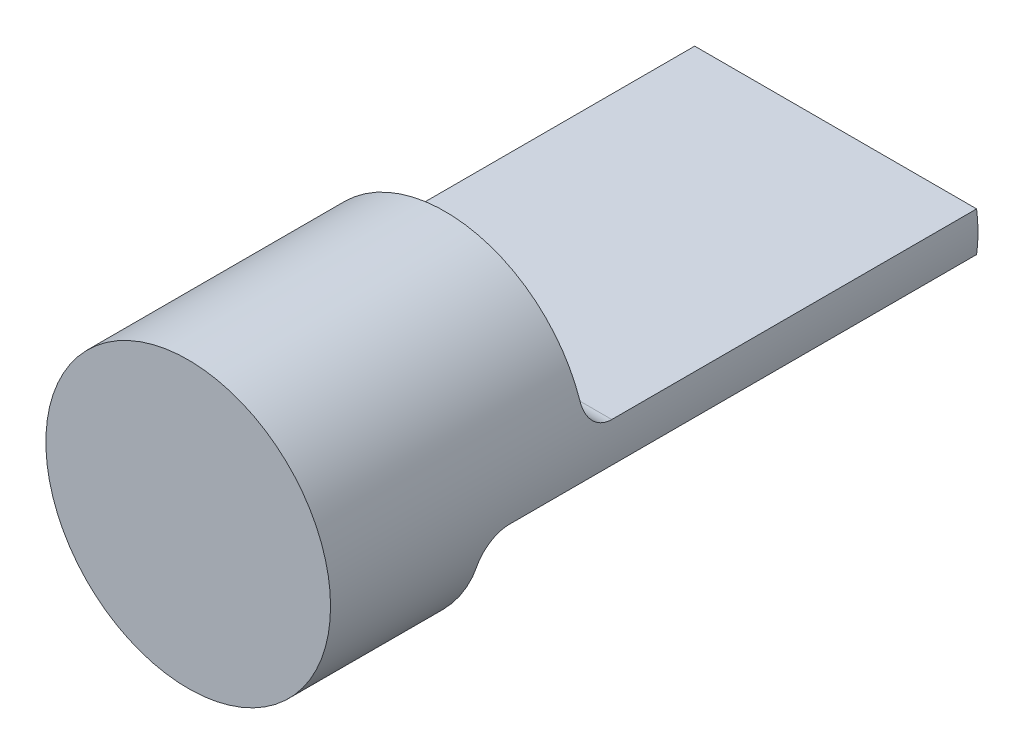
SolidWorks part; units mm, degrees
ref_plane "Front Plane" through (0, 0, 0) normal (0, 0, 1) x (1, 0, 0)
ref_plane "Top Plane" through (0, 0, 0) normal (0, 1, 0) x (1, 0, 0)
ref_plane "Right Plane" through (0, 0, 0) normal (1, 0, 0) x (0, 0, -1)
sketch "Sketch1" plane through (0, 0, 0) normal (0, 0, 1) x (1, 0, 0)
  circle A0 centre (0, 0) radius 13.85
  dimension "D1" = 27.7
extrude "Boss-Extrude1" add sketch "Sketch1" along normal blind 63
sketch "Sketch3" plane through (0, 0, 0) normal (1, 0, 0) x (0, 0, -1)
  line L0 (0, 1.925) -> (-35.5, 1.925)
  line L1 (0, -13.85) -> (0, 13.85) construction
  line L2 (0, 13.85) -> (-63, 13.85) construction
  line L3 (-38, 13.85) -> (0, 13.85)
  line L4 (0, 13.85) -> (0, 1.925)
  line L5 (0, -1.925) -> (-45.5, -1.925)
  line L6 (-63, -13.85) -> (0, -13.85) construction
  line L7 (-48, -13.85) -> (0, -13.85)
  line L8 (0, -13.85) -> (0, -1.925)
  line L9 (-48, -13.85) -> (-48, -4.425)
  line L10 (-38, 4.425) -> (-38, 13.85)
  line L11 (0, -1.925) -> (0, 1.925) construction
  arc A0 (-35.5, 1.925) -> (-38, 4.425) centre (-35.5, 4.425) cw
  arc A1 (-45.5, -1.925) -> (-48, -4.425) centre (-45.5, -4.425) ccw
  point P5 (0, 0)
  dimension "D2" = 2.5
  dimension "D1" = 48
  dimension "D3" = 38
  dimension "D4" = 3.85
extrude "Cut-Extrude1" cut sketch "Sketch3" against normal through all both and the other way through all
equation "\"SolenoidLength\"= 28mm"
equation "\"SolenoidWidth\"= 28"
equation "\"SolenoidLipLength\"= 10mm"
equation "\"D1@Sketch3\"=\"SolenoidLength\"+\"SolenoidLipLength\"+10"
equation "\"D3@Sketch3\"=\"SolenoidLength\"+10"
